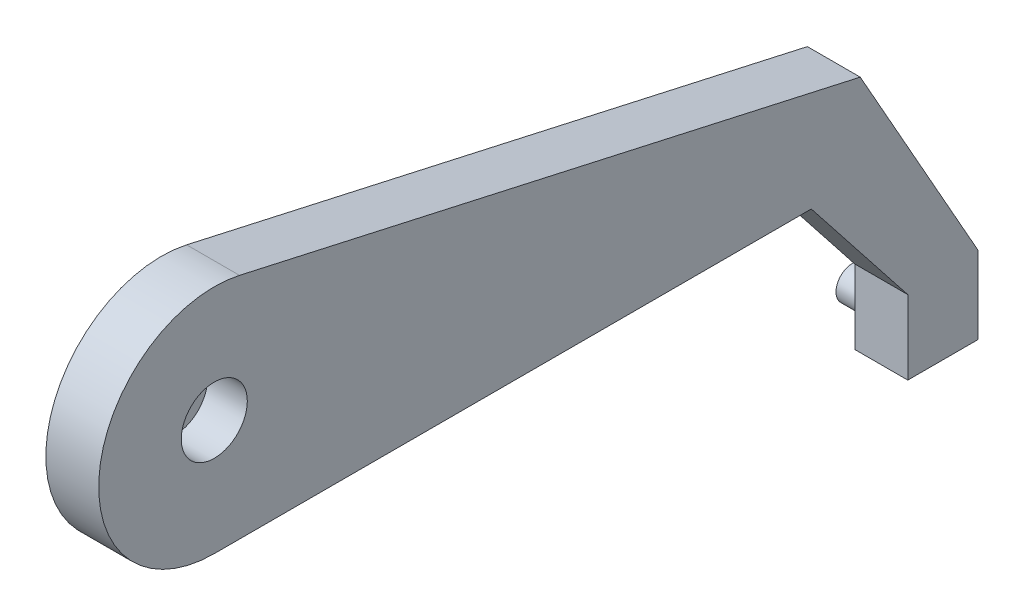
SolidWorks part; units mm, degrees
ref_plane "Front Plane" through (0, 0, 0) normal (0, 0, 1) x (1, 0, 0)
ref_plane "Top Plane" through (0, 0, 0) normal (0, 1, 0) x (1, 0, 0)
ref_plane "Right Plane" through (0, 0, 0) normal (1, 0, 0) x (0, 0, -1)
sketch "Sketch4" plane through (0, 0, 0) normal (1, 0, 0) x (0, 0, -1)
  line L7 (886.6661, 298.2975) -> (886.6661, 60.2159) construction
  line L8 (1320.8986, 319.5192) -> (2260.6275, 109.5586)
  line L9 (2260.6275, 109.5586) -> (2438.9246, -206.4808)
  line L10 (2438.9246, -206.4808) -> (2438.9246, -323.7302)
  line L11 (2438.9246, -323.7302) -> (2332.6589, -323.7302)
  line L12 (2332.6589, -323.7302) -> (2332.6589, -211.6307)
  line L13 (2332.6589, -211.6307) -> (2186.5348, -26.2698)
  line L14 (2186.5348, -26.2698) -> (1282.7398, -26.2698)
  arc A1 (1320.8986, 319.5192) -> (1282.7398, -26.2698) centre (1282.7398, 148.7302) ccw
sketch "Sketch5" plane through (0, 0, 0) normal (1, 0, 0) x (0, 0, -1)
  line L0 (1018.3318, 700.6598) -> (1018.3318, -249.3874) construction
extrude "Boss-Extrude3" add sketch "Sketch4" along normal blind 80
sketch "Sketch6" plane through (80, 0, 0) normal (1, 0, 0) x (0, 0, -1)
  circle A0 centre (1282.7398, 148.7302) radius 50
  dimension "D1" = 100
extrude "Cut-Extrude2" cut sketch "Sketch6" against normal blind 60
sketch "Sketch7" plane through (0, 0, 0) normal (-1, 0, 0) x (0, 0, 1)
  line L0 (-2332.6589, -323.7302) -> (-2438.9246, -323.7302) construction
  line L1 (-2438.9246, -323.7302) -> (-2438.9246, -206.4808) construction
  circle A0 centre (-2378.9246, -283.7302) radius 25
  dimension "D1" = 50
  dimension "D2" = 40
  dimension "D3" = 60
extrude "Boss-Extrude4" add sketch "Sketch7" along normal blind 50
